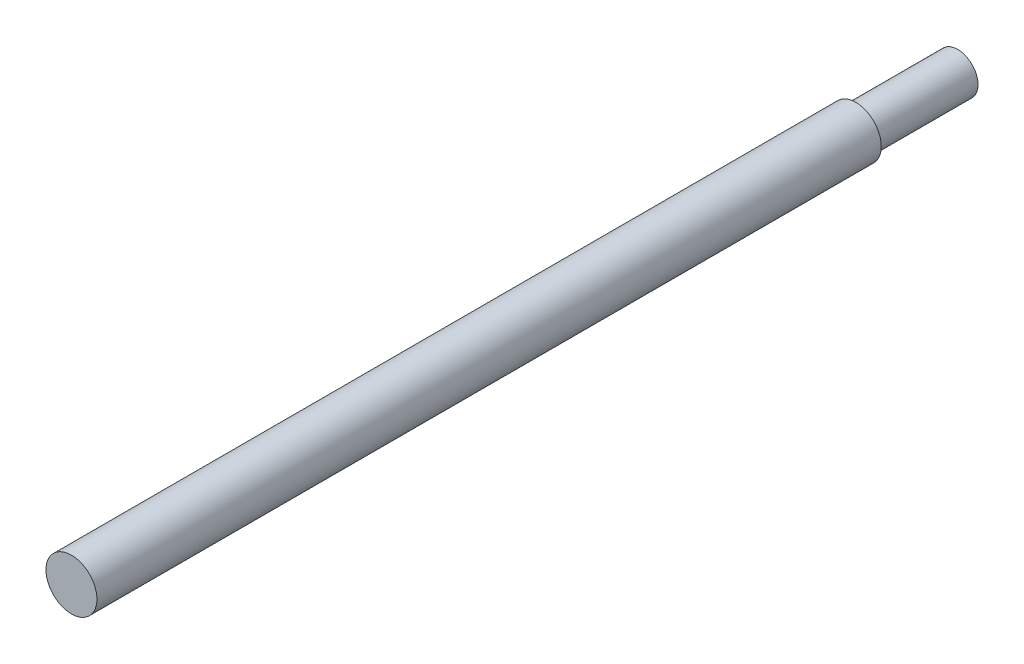
SolidWorks part; units mm, degrees
ref_plane "Plan de face" through (0, 0, 0) normal (0, 0, 1) x (1, 0, 0)
ref_plane "Plan de dessus" through (0, 0, 0) normal (0, 1, 0) x (1, 0, 0)
ref_plane "Plan de droite" through (0, 0, 0) normal (1, 0, 0) x (0, 0, -1)
sketch "Esquisse1" plane through (0, 0, 0) normal (0, 0, 1) x (1, 0, 0)
  circle A0 centre (0, 0) radius 2.5
  dimension "D1" = 5
extrude "Boss.-Extru.1" add sketch "Esquisse1" along normal blind 87
sketch "Esquisse2" plane through (0, 0, 0) normal (1, 0, 0) x (0, 0, -1)
  line L0 (0, 0) -> (-6.2259, 0) construction
  line L1 (0, 2.5) -> (-10, 2.5)
  line L2 (0, 2.5) -> (0, 2)
  line L3 (0, 2) -> (-10, 2)
  line L4 (-10, 2.5) -> (-10, 2)
  dimension "D1" = 0.5
  dimension "D2" = 10
revolve "Enlèvement de matière-Révolution1" cut sketch "Esquisse2" angle 360 about L0
